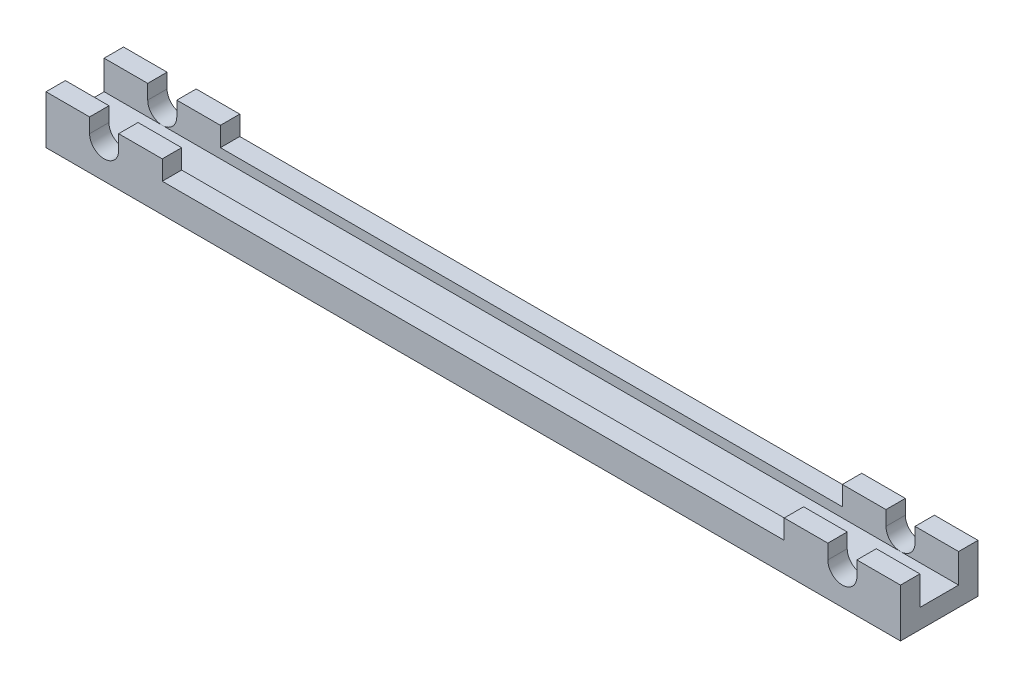
SolidWorks part; units mm, degrees
ref_plane "Front Plane" through (0, 0, 0) normal (0, 0, 1) x (1, 0, 0)
ref_plane "Top Plane" through (0, 0, 0) normal (0, 1, 0) x (1, 0, 0)
ref_plane "Right Plane" through (0, 0, 0) normal (1, 0, 0) x (0, 0, -1)
sketch "Sketch1" plane through (0, 0, 0) normal (0, 1, 0) x (1, 0, 0)
  line L1 (0, -4) -> (44.1, -4)
  line L2 (0, -4) -> (0, 4)
  line L3 (0, 4) -> (44.1, 4)
  line L4 (44.1, -4) -> (44.1, 4)
  point P4 (0, 0)
  dimension "D1" = 44.1
  dimension "D2" = 8
extrude "Boss-Extrude1" add sketch "Sketch1" along normal blind 2
sketch "Sketch2" plane through (0, 2, 0) normal (0, 1, 0) x (1, 0, 0)
  line L1 (44.1, 4) -> (32.1, 4)
  line L2 (44.1, 4) -> (44.1, 2)
  line L3 (44.1, 2) -> (32.1, 2)
  line L4 (32.1, 4) -> (32.1, 2)
  line L5 (44.1, -4) -> (32.1, -4)
  line L6 (44.1, -4) -> (44.1, -2)
  line L7 (44.1, -2) -> (32.1, -2)
  line L8 (32.1, -4) -> (32.1, -2)
  dimension "D1" = 2
  dimension "D2" = 12
extrude "Boss-Extrude2" add sketch "Sketch2" along normal blind 3
sketch "Sketch3" plane through (0, 0, 4) normal (0, 0, 1) x (1, 0, 0)
  line L0 (44.1, 5) -> (44.1, 0) construction
  line L1 (32.1, 5) -> (44.1, 5) construction
  line L2 (36.6, 3.5) -> (36.6, 5)
  line L3 (36.6, 5) -> (39.6, 5)
  line L4 (39.6, 5) -> (39.6, 3.5)
  arc A0 (36.6, 3.5) -> (39.6, 3.5) centre (38.1, 3.5) ccw
  dimension "D1" = 3
  dimension "D2" = 6
  dimension "D3" = 1.5
extrude "Cut-Extrude1" cut sketch "Sketch3" against normal through all
sketch "Sketch4" plane through (0, 2, 0) normal (0, 1, 0) x (1, 0, 0)
  line L0 (0, 4) -> (0, -4) construction
  line L1 (32.1, -4) -> (0, -4)
  line L2 (32.1, -4) -> (32.1, -2)
  line L3 (32.1, -2) -> (0, -2)
  line L4 (0, -4) -> (0, -2)
  line L6 (32.1, 2) -> (0, 2)
  line L7 (32.1, 2) -> (32.1, 4)
  line L8 (32.1, 4) -> (0, 4)
  line L9 (0, 2) -> (0, 4)
extrude "Boss-Extrude3" add sketch "Sketch4" along normal blind 1
mirror "Mirror1" about plane through (0, 0, 0) normal (1, 0, 0) of "Boss-Extrude3", "Cut-Extrude1", "Boss-Extrude2", "Boss-Extrude1"
